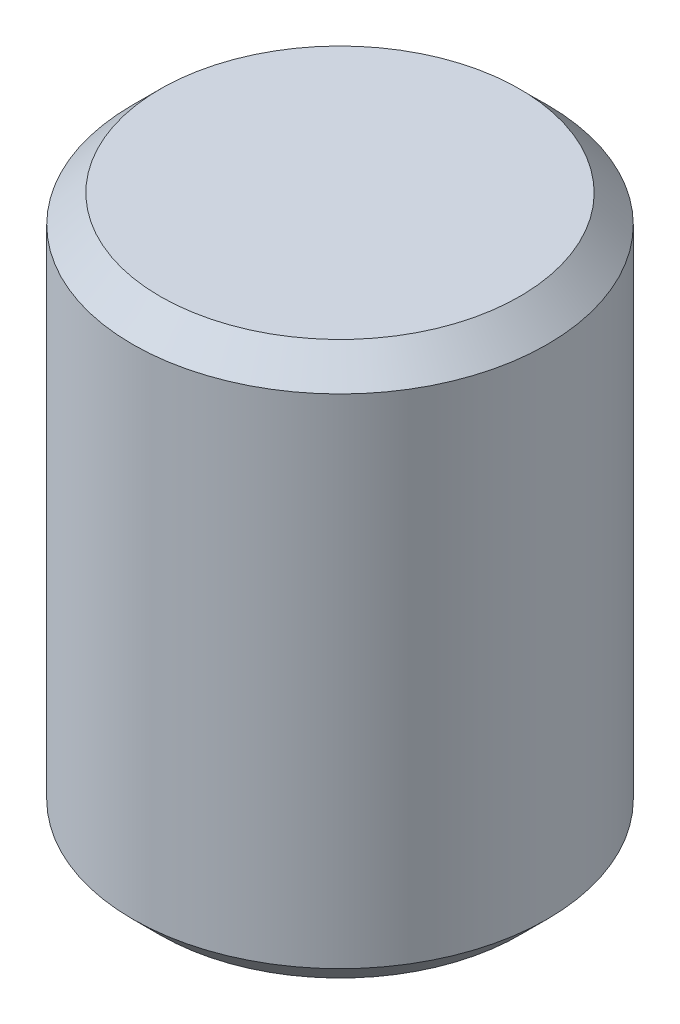
SolidWorks part; units mm, degrees
material "Сплав 1060"
ref_plane "Спереди" through (0, 0, 0) normal (0, 0, 1) x (1, 0, 0)
ref_plane "Сверху" through (0, 0, 0) normal (0, 1, 0) x (1, 0, 0)
ref_plane "Справа" through (0, 0, 0) normal (1, 0, 0) x (0, 0, -1)
sketch "Эскиз1" plane through (0, 0, 0) normal (0, 1, 0) x (1, 0, 0)
  circle A0 centre (0, 0) radius 15
  dimension "D1" = 30
extrude "Бобышка-Вытянуть1" add sketch "Эскиз1" along normal blind 40
chamfer "Фаска1" distance 2 angle 45 2 edges at (0, 0, 15) (0, 40, 15)
